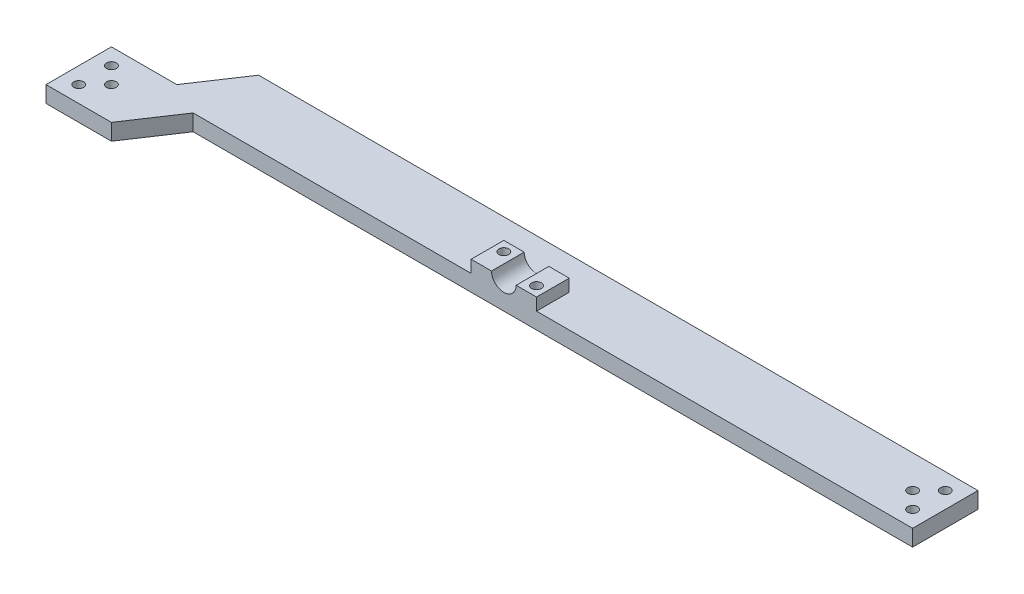
SolidWorks part; units mm, degrees
ref_plane "Front Plane" through (0, 0, 0) normal (0, 0, 1) x (1, 0, 0)
ref_plane "Top Plane" through (0, 0, 0) normal (0, 1, 0) x (1, 0, 0)
ref_plane "Right Plane" through (0, 0, 0) normal (1, 0, 0) x (0, 0, -1)
sketch "Sketch1" plane through (0, 0, 0) normal (0, 1, 0) x (1, 0, 0)
  line L0 (-32.5185, 35) -> (187.4815, 35)
  line L1 (187.4815, 35) -> (187.4815, 15)
  line L2 (187.4815, 15) -> (-32.5185, 15)
  line L3 (-32.5185, 15) -> (-42.5185, 0)
  line L4 (-42.5185, 0) -> (-62.5185, 0)
  line L5 (-62.5185, 0) -> (-62.5185, 20)
  line L6 (-62.5185, 20) -> (-42.5185, 20)
  line L7 (-42.5185, 20) -> (-32.5185, 35)
  dimension "D1" = 20
  dimension "D2" = 20
  dimension "D3" = 20
  dimension "D4" = 220
  dimension "D5" = 20
  dimension "D6" = 220
  dimension "D7" = 15
  dimension "D8" = 10
extrude "Boss-Extrude1" add sketch "Sketch1" along normal blind 5
sketch "Sketch2" plane through (0, 5, 0) normal (0, 1, 0) x (1, 0, 0)
  line L0 (-32.5185, 15) -> (187.4815, 15) construction
  line L1 (52.4815, 15) -> (72.4815, 15)
  line L2 (52.4815, 15) -> (52.4815, 25)
  line L3 (52.4815, 25) -> (72.4815, 25)
  line L4 (72.4815, 15) -> (72.4815, 25)
  line L5 (187.4815, 15) -> (187.4815, 35) construction
  dimension "D1" = 20
  dimension "D2" = 10
  dimension "D3" = 115
extrude "Boss-Extrude2" add sketch "Sketch2" along normal blind 3.75
sketch "Sketch3" plane through (0, 0, -25) normal (0, 0, -1) x (-1, 0, 0)
  line L0 (-72.4815, 8.75) -> (-52.4815, 8.75) construction
  line L1 (-52.4815, 8.75) -> (-52.4815, 5) construction
  circle A0 centre (-62.4815, 8.75) radius 3.775
  dimension "D1" = 7.55
  dimension "D2" = 0
  dimension "D3" = 10
extrude "Cut-Extrude1" cut sketch "Sketch3" against normal blind 10
sketch "Sketch4" plane through (0, 5, 0) normal (0, 1, 0) x (1, 0, 0)
  line L0 (72.4815, 15) -> (187.4815, 15) construction
  line L1 (187.4815, 35) -> (-32.5185, 35) construction
  line L2 (187.4815, 15) -> (187.4815, 35) construction
  line L3 (-42.5185, 20) -> (-62.5185, 20) construction
  line L4 (-62.5185, 0) -> (-42.5185, 0) construction
  line L5 (-62.5185, 20) -> (-62.5185, 0) construction
  circle A0 centre (182.4815, 20) radius 1.5
  circle A1 centre (177.4815, 25) radius 1.5
  circle A2 centre (182.4815, 30) radius 1.5
  circle A3 centre (-57.5185, 5) radius 1.5
  circle A4 centre (-57.5185, 15) radius 1.5
  circle A5 centre (-52.5185, 10) radius 1.5
  dimension "D1" = 3
  dimension "D2" = 3
  dimension "D3" = 3
  dimension "D4" = 10
  dimension "D5" = 5
  dimension "D6" = 5
  dimension "D7" = 5
  dimension "D8" = 5
  dimension "D9" = 10
  dimension "D10" = 3
  dimension "D11" = 3
  dimension "D12" = 3
  dimension "D13" = 5
  dimension "D14" = 5
  dimension "D15" = 5
  dimension "D16" = 5
  dimension "D17" = 10
  dimension "D18" = 10
extrude "Cut-Extrude2" cut sketch "Sketch4" against normal blind 5
sketch "Sketch5" plane through (0, 8.75, 0) normal (0, 1, 0) x (1, 0, 0)
  line L0 (72.4815, 15) -> (72.4815, 25) construction
  line L2 (52.4815, 25) -> (52.4815, 15) construction
  line L4 (66.2565, 15) -> (72.4815, 15) construction
  line L5 (58.7065, 25) -> (52.4815, 25) construction
  circle A0 centre (55.4815, 22) radius 1.5
  circle A1 centre (69.4815, 18) radius 1.5
  dimension "D1" = 3
  dimension "D2" = 3
  dimension "D3" = 3
  dimension "D4" = 3
  dimension "D5" = 3
  dimension "D6" = 3
extrude "Cut-Extrude3" cut sketch "Sketch5" against normal blind 4
